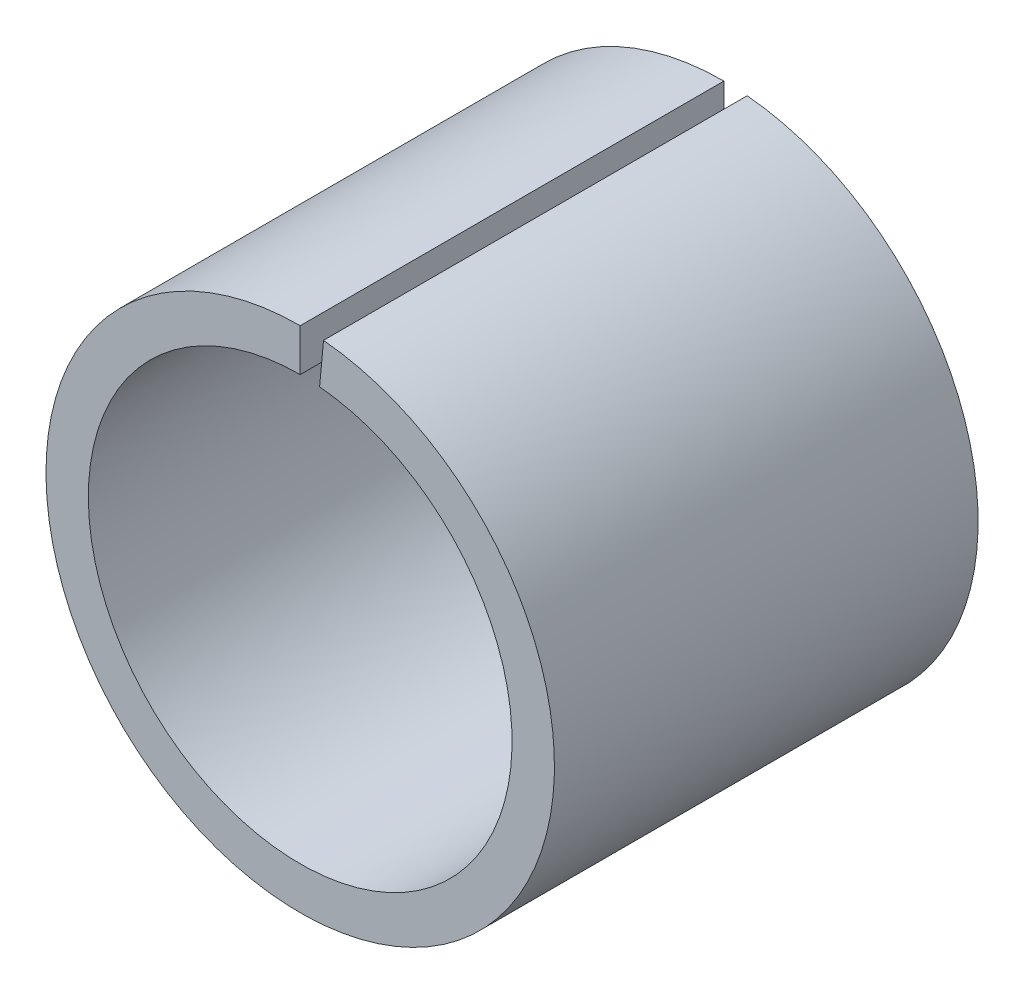
SolidWorks part; units mm, degrees
ref_plane "前视基准面" through (0, 0, 0) normal (0, 0, 1) x (1, 0, 0)
ref_plane "上视基准面" through (0, 0, 0) normal (0, 1, 0) x (1, 0, 0)
ref_plane "右视基准面" through (0, 0, 0) normal (1, 0, 0) x (0, 0, -1)
sketch "草图1" plane through (0, 0, 0) normal (0, 0, 1) x (1, 0, 0)
  circle A0 centre (0, 0) radius 6
  circle A1 centre (0, 0) radius 5
  dimension "D1" = 10
  dimension "D2" = 12
extrude "凸台-拉伸1" add sketch "草图1" along normal blind 10
sketch "草图2" plane through (0, 0, 10) normal (0, 0, 1) x (1, 0, 0)
  line L0 (0, 0) -> (0, 6)
  line L1 (0, 6) -> (0.5876, 6.3861)
  line L2 (0.5876, 6.3861) -> (0, 0)
  circle A0 centre (0, 0) radius 6 construction
extrude "切除-拉伸1" cut sketch "草图2" against normal blind 20
